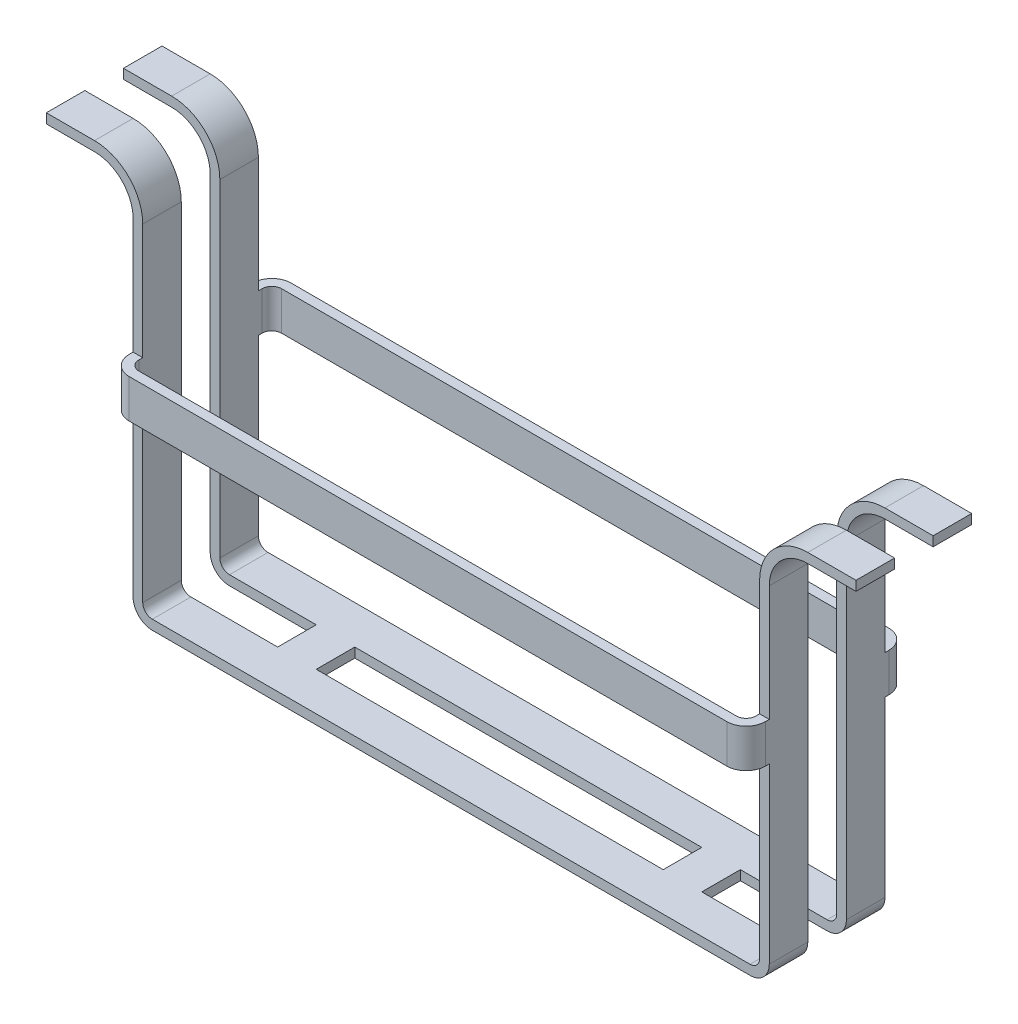
SolidWorks part; units mm, degrees
ref_plane "前视基准面" through (0, 0, 0) normal (0, 0, 1) x (1, 0, 0)
ref_plane "上视基准面" through (0, 0, 0) normal (0, 1, 0) x (1, 0, 0)
ref_plane "右视基准面" through (0, 0, 0) normal (1, 0, 0) x (0, 0, -1)
sketch "草图1" plane through (0, 0, 0) normal (0, 0, 1) x (1, 0, 0)
  line L0 (0, 0) -> (0, 150.5995) construction
  line L1 (155, 0) -> (-155, 0)
  line L2 (-165, 10) -> (-165, 180)
  line L3 (-185, 200) -> (-210, 200)
  line L4 (185, 200) -> (210, 200)
  line L5 (165, 10) -> (165, 180)
  arc A0 (-155, 0) -> (-165, 10) centre (-155, 10) cw
  arc A1 (-165, 180) -> (-185, 200) centre (-185, 180) ccw
  arc A2 (165, 180) -> (185, 200) centre (185, 180) cw
  arc A3 (155, 0) -> (165, 10) centre (155, 10) ccw
  point P6 (-116.7015, 200)
  point P9 (-165, 0)
  point P12 (-165, 200)
  point P20 (165, 200)
  point P21 (165, 0)
  dimension "D3" = 10
  dimension "D4" = 20
  dimension "D1" = 200
  dimension "D2" = 420
  dimension "D5" = 45
extrude "拉伸-薄壁1" add sketch "草图1" along normal blind 20 thin
ref_plane "基准面1" through (0, 100, 0) normal (0, 1, 0) x (1, 0, 0)
sketch "草图2" plane through (0, 100, 0) normal (0, 1, 0) x (1, 0, 0)
  line L0 (-165, -20) -> (-165, -22)
  line L1 (-155, -32) -> (155, -32)
  line L2 (-165, -20) -> (-165, 0) construction
  line L3 (-155, -20) -> (155, -20) construction
  line L4 (0, 0) -> (0, -32) construction
  line L5 (165, -20) -> (165, -22)
  arc A0 (-165, -22) -> (-155, -32) centre (-155, -22) ccw
  arc A1 (165, -22) -> (155, -32) centre (155, -22) cw
  point P14 (-165, -20)
  dimension "D2" = 10
  dimension "D1" = 12
extrude "拉伸-薄壁2" add sketch "草图2" along normal blind 20 thin wall 5
ref_plane "基准面2" through (0, 0, -10) normal (0, 0, 1) x (1, 0, 0)
mirror "镜向3" about plane through (0, 0, -10) normal (0, 0, 1) of bodies 102
sketch "草图3" plane through (0, 5, 0) normal (0, 1, 0) x (1, 0, 0)
  line L0 (-155, 20) -> (155, 20) construction
  line L1 (-110, 20) -> (-90, 20)
  line L2 (-110, 20) -> (-110, 0)
  line L3 (-110, 0) -> (-90, 0)
  line L4 (-90, 20) -> (-90, 0)
  line L5 (-155, 0) -> (155, 0) construction
  dimension "D1" = 20
  dimension "D2" = 90
extrude "凸台-拉伸1" add sketch "草图3" against normal up to surface (5 mm away) up to face at (0, 0, -30)
mirror "镜向4" about plane through (0, 0, 0) normal (1, 0, 0) of "凸台-拉伸1"
